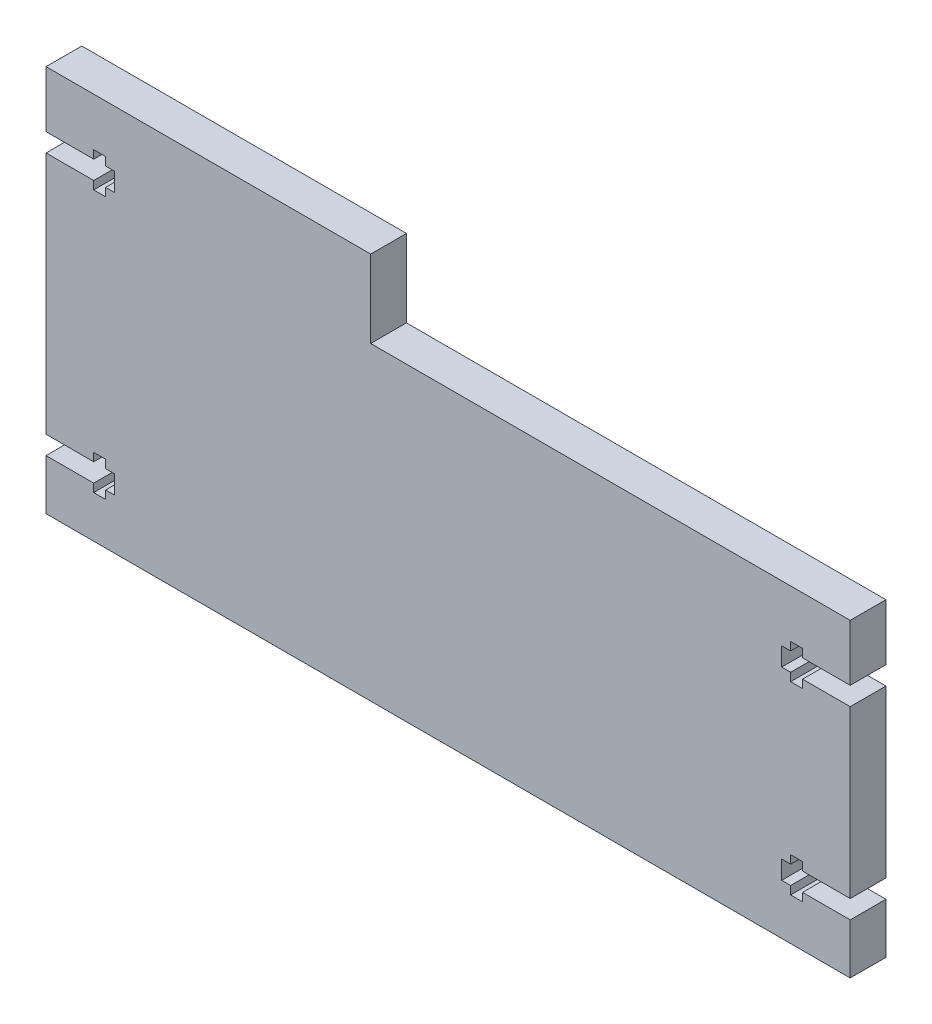
SolidWorks part; units mm, degrees
ref_plane "Płaszczyzna przednia" through (0, 0, 0) normal (0, 0, 1) x (1, 0, 0)
ref_plane "Płaszczyzna górna" through (0, 0, 0) normal (0, 1, 0) x (1, 0, 0)
ref_plane "Płaszczyzna prawa" through (0, 0, 0) normal (1, 0, 0) x (0, 0, -1)
sketch "Szkic1" plane through (0, 0, 0) normal (0, 0, 1) x (1, 0, 0)
  line L0 (363.1317, 294.7554) -> (363.1317, 229.7554)
  line L1 (363.1317, 294.7554) -> (498.1317, 294.7554)
  line L2 (363.1317, 229.7554) -> (498.1317, 229.7554)
  line L3 (498.1317, 294.7554) -> (498.1317, 229.7554)
  dimension "D1" = 135
  dimension "D2" = 65
extrude "Dodanie-wyciągnięcie1" add sketch "Szkic1" along normal blind 6
sketch "Szkic2" plane through (0, 0, 6) normal (0, 0, 1) x (1, 0, 0)
  line L0 (363.1317, 241.3054) -> (363.1317, 238.2054)
  line L1 (363.1317, 241.3054) -> (371.1317, 241.3054)
  line L2 (363.1317, 238.2054) -> (371.1317, 238.2054)
  line L3 (374.6317, 241.3054) -> (374.6317, 238.2054)
  line L4 (363.1317, 294.7554) -> (363.1317, 229.7554) construction
  line L5 (371.1317, 242.6804) -> (371.1317, 241.3054)
  line L6 (371.1317, 242.6804) -> (373.1317, 242.6804)
  line L7 (371.1317, 236.8304) -> (373.1317, 236.8304)
  line L8 (373.1317, 242.6804) -> (373.1317, 241.3054)
  line L9 (371.1317, 238.2054) -> (371.1317, 236.8304)
  line L10 (373.1317, 241.3054) -> (374.6317, 241.3054)
  line L11 (373.1317, 238.2054) -> (373.1317, 236.8304)
  line L12 (373.1317, 238.2054) -> (374.6317, 238.2054)
  line L14 (363.1317, 229.7554) -> (498.1317, 229.7554) construction
  point P14 (363.1317, 239.7554)
  dimension "D1" = 11.5
  dimension "D2" = 3.1
  dimension "D3" = 5.85
  dimension "D4" = 2
  dimension "D5" = 1.375
  dimension "D6" = 1.5
  dimension "D7" = 10
extrude "Wytnij-wyciągnięcie1" cut sketch "Szkic2" against normal blind 6
pattern_linear "Szyk liniowy1" count 2 spacing 44 along (0, 1, 0) of "Wytnij-wyciągnięcie1"
ref_plane "Płaszczyzna1" through (430.6317, 0, 0) normal (-1, 0, 0) x (0, 0, 1)
mirror "Lustro1" about plane through (430.6317, 0, 0) normal (-1, 0, 0) of "Wytnij-wyciągnięcie1"
pattern_linear "Szyk liniowy2" count 2 spacing 31 along (0, 1, 0) of "Lustro1", "Wytnij-wyciągnięcie1"
sketch "Szkic3" plane through (0, 0, 6) normal (0, 0, 1) x (1, 0, 0)
  line L0 (363.1317, 277.2554) -> (378.7772, 277.2554)
  line L1 (363.1317, 277.2554) -> (363.1317, 267.8304)
  line L2 (378.7772, 277.2554) -> (378.7772, 267.8304)
  line L3 (363.1317, 267.8304) -> (378.7772, 267.8304)
  line L4 (363.1317, 282.2054) -> (363.1317, 272.3054) construction
  line L5 (371.1317, 267.8304) -> (373.1317, 267.8304) construction
  dimension "D1" = 0
extrude "Dodanie-wyciągnięcie2" add sketch "Szkic3" against normal blind 6
sketch "Szkic4" plane through (0, 0, 6) normal (0, 0, 1) x (1, 0, 0)
  line L0 (498.1317, 294.7554) -> (498.1317, 281.7554)
  line L1 (498.1317, 294.7554) -> (417.6317, 294.7554)
  line L2 (498.1317, 281.7554) -> (417.6317, 281.7554)
  line L3 (417.6317, 294.7554) -> (417.6317, 281.7554)
  line L4 (498.1317, 272.3054) -> (498.1317, 294.7554) construction
  dimension "D1" = 80.5
  dimension "D2" = 13
extrude "Wytnij-wyciągnięcie2" cut sketch "Szkic4" against normal blind 6
equation "\"tolerancja_wpusy\"=0.2"
equation "\"dlugosc_wpustu_duzy\"=20"
equation "\"srednica_otworu_M3\"=3.1"
equation "\"szerokosc_nogi_T\"=3.1"
equation "\"dlugosc_T_30\"=11"
equation "\"grubosc_na_nakretke_kwadrat\"=2"
equation "\"szerokosc_na_nakretke_kwadrat\"=5.85"
equation "\"wyokosc_nadstawki_T\"=0.5"
equation "\"dlugosc_T_20_6\"=14"
equation "\"D2@Szkic2\"=\"szerokosc_nogi_T\""
equation "\"D3@Szkic2\"=\"szerokosc_na_nakretke_kwadrat\""
equation "\"D4@Szkic2\"=\"grubosc_na_nakretke_kwadrat\""
equation "\"D5@Szkic2\"=(\"szerokosc_na_nakretke_kwadrat\"-\"szerokosc_nogi_T\")/2"
equation "\"D6@Szkic2\"=\"wyokosc_nadstawki_T\"+1"
